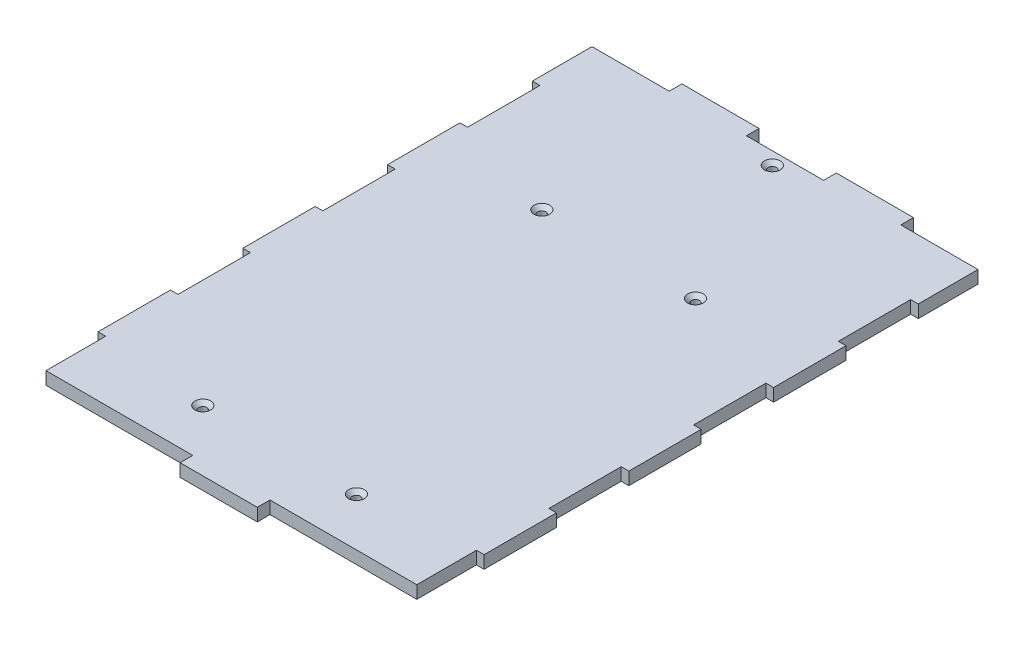
SolidWorks part; units mm, degrees
ref_plane "Front Plane" through (0, 0, 0) normal (0, 0, 1) x (1, 0, 0)
ref_plane "Top Plane" through (0, 0, 0) normal (0, 1, 0) x (1, 0, 0)
ref_plane "Right Plane" through (0, 0, 0) normal (1, 0, 0) x (0, 0, -1)
sketch "Sketch1" plane through (0, 0, 0) normal (0, 1, 0) x (1, 0, 0)
  line L0 (0, -114) -> (-15.2, -114)
  line L1 (-76, -114) -> (76, -114) construction
  line L2 (-76, -114) -> (-76, 114) construction
  line L3 (-76, 114) -> (76, 114) construction
  line L4 (76, -114) -> (76, 114) construction
  line L5 (0, 109) -> (0, -114)
  line L6 (-76, 0) -> (76, 0) construction
  line L7 (-15.2, -114) -> (-15.2, -109)
  line L8 (-15.2, -109) -> (-73, -109)
  line L25 (-73, -109) -> (-73, -85.5)
  line L26 (-73, -85.5) -> (-76, -85.5)
  line L27 (-76, -57) -> (-73, -57)
  line L28 (-73, -57) -> (-73, -28.5)
  line L29 (-73, -28.5) -> (-76, -28.5)
  line L30 (-76, -28.5) -> (-76, 0)
  line L31 (-76, -85.5) -> (-76, -57)
  line L32 (-76, 0) -> (-73, 0)
  line L33 (-73, 0) -> (-73, 28.5)
  line L34 (-73, 28.5) -> (-76, 28.5)
  line L35 (-76, 28.5) -> (-76, 57)
  line L36 (-76, 57) -> (-73, 57)
  line L37 (-73, 57) -> (-73, 85.5)
  line L38 (-73, 85.5) -> (-76, 85.5)
  line L42 (-76, 109) -> (-76, 85.5)
  line L43 (0, 109) -> (-15.2, 109)
  line L44 (-15.2, 109) -> (-15.2, 114)
  line L45 (-15.2, 114) -> (-45.6, 114)
  line L46 (-45.6, 114) -> (-45.6, 109)
  line L47 (-45.6, 109) -> (-76, 109)
  point P128 (0, 0)
  dimension "D1" = 152
  dimension "D2" = 228
  dimension "D5" = 5
  dimension "D3" = 60.8
  dimension "D4" = 28.5
  dimension "D6" = 3
  dimension "D7" = 28.5
  dimension "D8" = 28.5
  dimension "D9" = 28.5
  dimension "D10" = 28.5
  dimension "D11" = 28.5
  dimension "D12" = 28.5
  dimension "D13" = 5
  dimension "D14" = 30.4
extrude "Boss-Extrude1" add sketch "Sketch1" along normal blind 5
mirror "Mirror1" about plane through (0, 5, 0) normal (1, 0, 0) of "Boss-Extrude1"
sketch "Sketch2" plane through (0, 5, 0) normal (0, 1, 0) x (1, 0, 0)
  line L0 (15.2, 109) -> (-15.2, 109) construction
  circle A0 centre (0, 104) radius 1.6
  dimension "D2" = 3.2
  dimension "D1" = 5
extrude "Cut-Extrude1" cut sketch "Sketch2" against normal through all
sketch "Sketch3" plane through (0, 5, 0) normal (0, 1, 0) x (1, 0, 0)
  line L0 (15.2, -109) -> (73, -109) construction
  line L1 (30.25, -90) -> (-30.25, -90) construction
  line L2 (30.25, -90) -> (30.25, 43.5) construction
  line L3 (30.25, 43.5) -> (-30.25, 43.5) construction
  line L4 (-30.25, -90) -> (-30.25, 43.5) construction
  line L5 (0, 43.5) -> (0, -90) construction
  line L6 (30.25, -23.25) -> (-30.25, -23.25) construction
  circle A0 centre (-30.25, -90) radius 1.6
  circle A1 centre (-30.25, 43.5) radius 1.6
  circle A2 centre (30.25, 43.5) radius 1.6
  circle A3 centre (30.25, -90) radius 1.6
  point P152 (0, -23.25)
  dimension "D1" = 3.2
  dimension "D2" = 60.5
  dimension "D3" = 133.5
  dimension "D4" = 19
extrude "Cut-Extrude2" cut sketch "Sketch3" against normal through all
chamfer "Chamfer1" distance 1.5 5 edges at (0, 5, -102.4) (30.25, 5, -41.9) (30.25, 5, 91.6) (-30.25, 5, 91.6) (-30.25, 5, -41.9)
equation "\"3mm akryyli\"= 3mm"
equation "\"5mm akryyli\"= 5mm"
equation "\"D5@Sketch1\"=\"5mm akryyli\""
equation "\"D6@Sketch1\"=\"3mm akryyli\""
equation "\"D13@Sketch1\"=\"5mm akryyli\""
